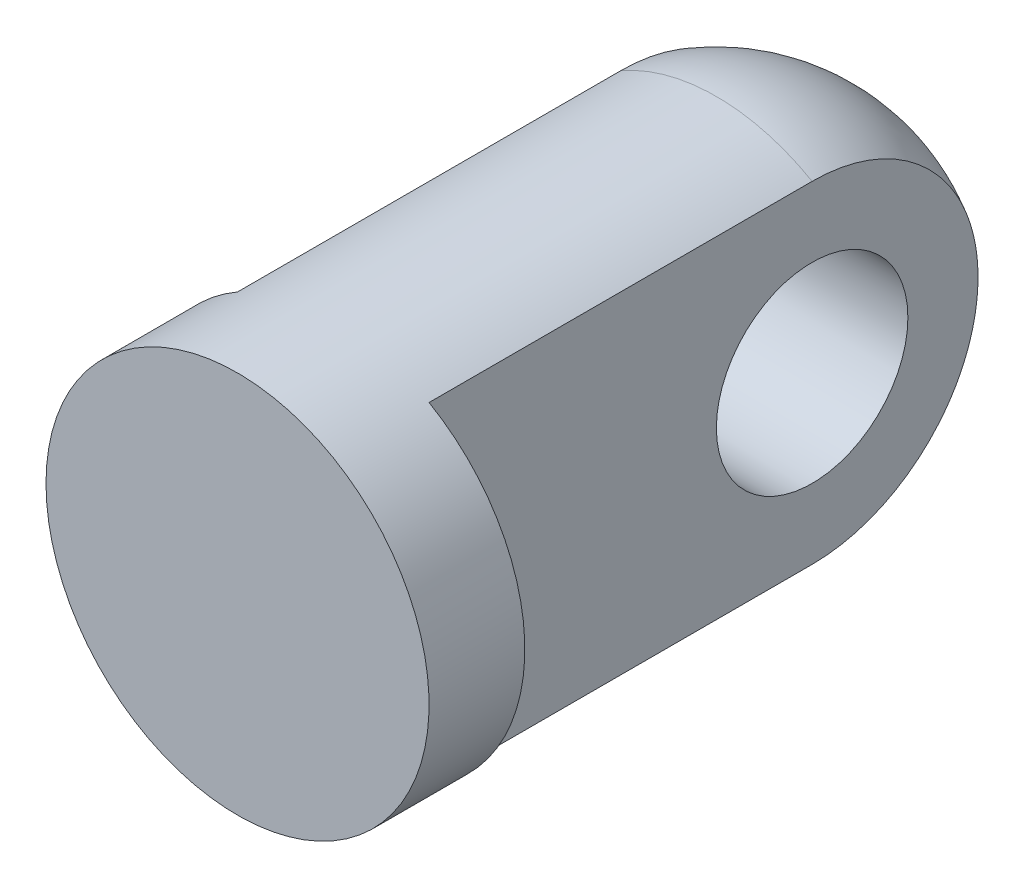
SolidWorks part; units mm, degrees
ref_plane "Front Plane" through (0, 0, 0) normal (0, 0, 1) x (1, 0, 0)
ref_plane "Top Plane" through (0, 0, 0) normal (0, 1, 0) x (1, 0, 0)
ref_plane "Right Plane" through (0, 0, 0) normal (1, 0, 0) x (0, 0, -1)
sketch "Sketch1" plane through (0, 0, 0) normal (0, 1, 0) x (1, 0, 0)
  line L3 (0, 0) -> (0, 15.875)
  line L4 (0, 0) -> (6.35, 0)
  line L5 (6.35, 0) -> (6.35, 15.875)
  line L6 (0, 22.225) -> (0, 15.875)
  arc A3 (6.35, 15.875) -> (0, 22.225) centre (0, 15.875) ccw
  dimension "D1" = 6.35
  dimension "D3" = 15.875
revolve "Revolve1" add sketch "Sketch1" angle 360 about L6
sketch "Sketch2" plane through (0, 0, 0) normal (0, 1, 0) x (1, 0, 0)
  line L0 (-3.175, 63.1792) -> (-3.175, 3.175)
  line L1 (-3.175, 3.175) -> (-15.875, 3.175)
  line L2 (-15.875, 3.175) -> (-15.875, 63.1792)
  line L3 (-15.875, 63.1792) -> (-3.175, 63.1792)
  line L5 (-6.35, 0) -> (6.35, 0) construction
  dimension "D1" = 12.7
  dimension "D2" = 3.175
  dimension "D3" = 3.175
extrude "Cut-Extrude1" cut sketch "Sketch2" against normal through all and the other way through all
mirror "Mirror1" about plane through (0, 0, 0) normal (1, 0, 0) of "Cut-Extrude1"
sketch "Sketch3" plane through (-3.175, 0, 0) normal (-1, 0, 0) x (0, 0, 1)
  circle A0 centre (-15.875, 0) radius 3.175
  arc A1 (-15.875, 5.4993) -> (-15.875, -5.4993) centre (-15.875, 0) ccw construction
  dimension "D1" = 6.35
extrude "Cut-Extrude2" cut sketch "Sketch3" against normal through all
